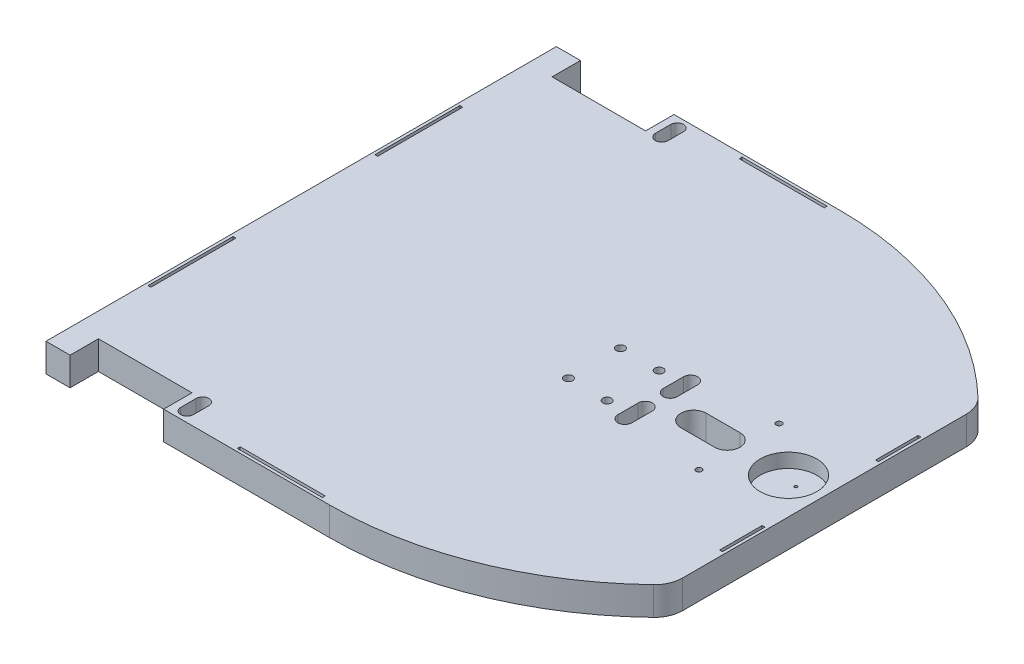
SolidWorks part; units mm, degrees
ref_plane "Front Plane" through (0, 0, 0) normal (0, 0, 1) x (1, 0, 0)
ref_plane "Top Plane" through (0, 0, 0) normal (0, 1, 0) x (1, 0, 0)
ref_plane "Right Plane" through (0, 0, 0) normal (1, 0, 0) x (0, 0, -1)
sketch "Sketch1" plane through (0, 0, 0) normal (0, 1, 0) x (1, 0, 0)
  line L0 (-89.3891, 0) -> (95.1826, 0) construction
  line L1 (-89.3891, -90) -> (-89.3891, 90)
  line L2 (-89.3891, 90) -> (10.6109, 90)
  line L3 (95.1826, 50) -> (95.1826, -50)
  line L4 (-89.3891, -90) -> (10.6109, -90)
  arc A0 (10.6109, 90) -> (92.1078, 57.214) centre (10.6109, -27.6825) cw
  arc A1 (92.1078, 57.214) -> (95.1826, 50) centre (85.1826, 50) cw
  arc A2 (92.1078, -57.214) -> (95.1826, -50) centre (85.1826, -50) ccw
  arc A3 (10.6109, -90) -> (92.1078, -57.214) centre (10.6109, 27.6825) ccw
  dimension "D1" = 10
  dimension "D2" = 180
  dimension "D3" = 100
  dimension "D4" = 100
extrude "Boss-Extrude1" add sketch "Sketch1" along normal blind 10
sketch "Sketch2" plane through (0, 10, 0) normal (0, 1, 0) x (1, 0, 0)
  line L0 (-89.3891, 0) -> (95.1826, 0) construction
  line L1 (-89.3891, 90) -> (-89.3891, -90) construction
  line L2 (95.1826, -50) -> (95.1826, 50) construction
  line L4 (36.3663, -11.5949) -> (36.3663, -4.4051) construction
  line L7 (-43.2044, 86.4271) -> (-43.2044, 80.9729) construction
  line L8 (-40.9689, 86.4271) -> (-40.9689, 80.9729)
  line L9 (-45.4398, 86.4271) -> (-45.4398, 80.9729)
  line L10 (36.3663, 11.5949) -> (36.3663, 4.4051) construction
  line L11 (38.8455, 11.5949) -> (38.8455, 4.4051)
  line L12 (33.887, 11.5949) -> (33.887, 4.4051)
  line L14 (10.6109, 90) -> (-89.3891, 90) construction
  line L15 (-80.901, 90) -> (-47.901, 90)
  line L16 (-80.901, 90) -> (-80.901, 80)
  line L17 (-80.901, 80) -> (-47.901, 80)
  line L18 (-47.901, 90) -> (-47.901, 80)
  line L19 (38.8455, -11.5949) -> (38.8455, -4.4051)
  line L20 (33.887, -11.5949) -> (33.887, -4.4051)
  line L21 (-43.2044, -86.4271) -> (-43.2044, -80.9729) construction
  line L22 (-40.9689, -86.4271) -> (-40.9689, -80.9729)
  line L23 (-45.4398, -86.4271) -> (-45.4398, -80.9729)
  line L24 (-80.901, -80) -> (-47.901, -80)
  line L25 (-47.901, -90) -> (-47.901, -80)
  line L26 (-80.901, -90) -> (-47.901, -90)
  line L27 (-80.901, -90) -> (-80.901, -80)
  circle A0 centre (65, 14.1316) radius 1
  circle A1 centre (27.689, 9.1731) radius 1.5
  circle A2 centre (14.0532, 9.1731) radius 1.5
  arc A3 (-40.9689, 86.4271) -> (-45.4398, 86.4271) centre (-43.2044, 86.4271) ccw
  arc A4 (-45.4398, 80.9729) -> (-40.9689, 80.9729) centre (-43.2044, 80.9729) ccw
  arc A5 (38.8455, 11.5949) -> (33.887, 11.5949) centre (36.3663, 11.5949) ccw
  arc A6 (33.887, 4.4051) -> (38.8455, 4.4051) centre (36.3663, 4.4051) ccw
  circle A7 centre (14.0532, -9.1731) radius 1.5
  circle A8 centre (27.689, -9.1731) radius 1.5
  circle A9 centre (65, -14.1316) radius 1
  arc A10 (38.8455, -11.5949) -> (33.887, -11.5949) centre (36.3663, -11.5949) cw
  arc A11 (33.887, -4.4051) -> (38.8455, -4.4051) centre (36.3663, -4.4051) cw
  arc A12 (-40.9689, -86.4271) -> (-45.4398, -86.4271) centre (-43.2044, -86.4271) cw
  arc A13 (-45.4398, -80.9729) -> (-40.9689, -80.9729) centre (-43.2044, -80.9729) cw
  point P20 (-43.2044, 83.7)
  point P25 (36.3663, 8)
  point P32 (0, 0)
  point P41 (36.3663, -8)
  point P48 (-43.2044, -83.7)
  dimension "D1" = 10
  dimension "D2" = 33
extrude "Cut-Extrude2" cut sketch "Sketch2" against normal mid plane 30 contours L17 L18 L15 L16 | L24 L25 L26 L27 | L19 A11 L20 A10 | L11 A6 L12 A5 | A1 | A2 | A7 | A8 | A9 | A0 | L8 A4 L9 A3 | L22 A13 L23 A12
sketch "Sketch3" plane through (0, 10, 0) normal (0, 1, 0) x (1, 0, 0)
  line L0 (12.3178, 0) -> (112.2305, 0) construction
  circle A0 centre (82.4798, 0) radius 10
extrude "Cut-Extrude3" cut sketch "Sketch3" against normal mid plane 10
sketch "Sketch4" plane through (0, 10, 0) normal (0, 1, 0) x (1, 0, 0)
  line L0 (49.0103, 0) -> (60.9106, 0) construction
  line L1 (49.0103, 4.4626) -> (60.9106, 4.4626)
  line L2 (49.0103, -4.4626) -> (60.9106, -4.4626)
  arc A0 (49.0103, 4.4626) -> (49.0103, -4.4626) centre (49.0103, 0) ccw
  arc A1 (60.9106, -4.4626) -> (60.9106, 4.4626) centre (60.9106, 0) ccw
  point P3 (54.9604, 0)
extrude "Cut-Extrude4" cut sketch "Sketch4" against normal mid plane 30
sketch "Sketch5" plane through (0, 10, 0) normal (0, 1, 0) x (1, 0, 0)
  line L0 (10.6109, 90) -> (-47.901, 90) construction
  line L1 (-22.901, 89) -> (7.099, 89)
  line L2 (-22.901, 89) -> (-22.901, 88)
  line L3 (-22.901, 88) -> (7.099, 88)
  line L4 (7.099, 89) -> (7.099, 88)
  line L5 (-88.3891, 55) -> (-87.3891, 55)
  line L6 (-88.3891, 55) -> (-88.3891, 25)
  line L7 (-88.3891, 25) -> (-87.3891, 25)
  line L8 (-87.3891, 55) -> (-87.3891, 25)
  line L9 (93.1826, 35) -> (94.1826, 35)
  line L10 (93.1826, 35) -> (93.1826, 20)
  line L11 (93.1826, 20) -> (94.1826, 20)
  line L12 (94.1826, 35) -> (94.1826, 20)
  line L13 (95.1826, -50) -> (95.1826, 50) construction
  line L14 (-89.3891, 90) -> (-89.3891, -90) construction
  line L15 (-89.3891, 0) -> (94.1826, 0) construction
  line L16 (93.1826, -20) -> (94.1826, -20)
  line L17 (94.1826, -35) -> (94.1826, -20)
  line L18 (93.1826, -35) -> (94.1826, -35)
  line L19 (93.1826, -35) -> (93.1826, -20)
  line L20 (-22.901, -88) -> (7.099, -88)
  line L21 (7.099, -89) -> (7.099, -88)
  line L22 (-22.901, -89) -> (7.099, -89)
  line L23 (-22.901, -89) -> (-22.901, -88)
  line L24 (-88.3891, -25) -> (-87.3891, -25)
  line L25 (-87.3891, -55) -> (-87.3891, -25)
  line L26 (-88.3891, -55) -> (-87.3891, -55)
  line L27 (-88.3891, -55) -> (-88.3891, -25)
  line L28 (-47.901, 80) -> (-47.901, 90) construction
  dimension "D1" = 1
  dimension "D2" = 30
  dimension "D3" = 1
  dimension "D4" = 30
  dimension "D5" = 1
  dimension "D6" = 15
  dimension "D7" = 1
  dimension "D8" = 1
  dimension "D9" = 1
  dimension "D10" = 25
  dimension "D11" = 20
  dimension "D12" = 20
  dimension "D13" = 25
extrude "Cut-Extrude6" cut sketch "Sketch5" against normal mid plane 30 contours L6 L7 L8 L5 | L1 L4 L3 L2 | L10 L11 L12 L9 | L17 L16 L19 L18 | L20 L21 L22 L23 | L25 L24 L27 L26
sketch "Sketch6" plane through (0, 5, 0) normal (0, 1, 0) x (1, 0, 0)
  circle A0 centre (82.2441, 2.8356) radius 0.5
  circle A1 centre (82.2441, -5.1644) radius 0.5
  point P6 (0, 0)
  dimension "D1" = 8
extrude "Cut-Extrude7" cut sketch "Sketch6" against normal mid plane 30 contours A1 | A0
